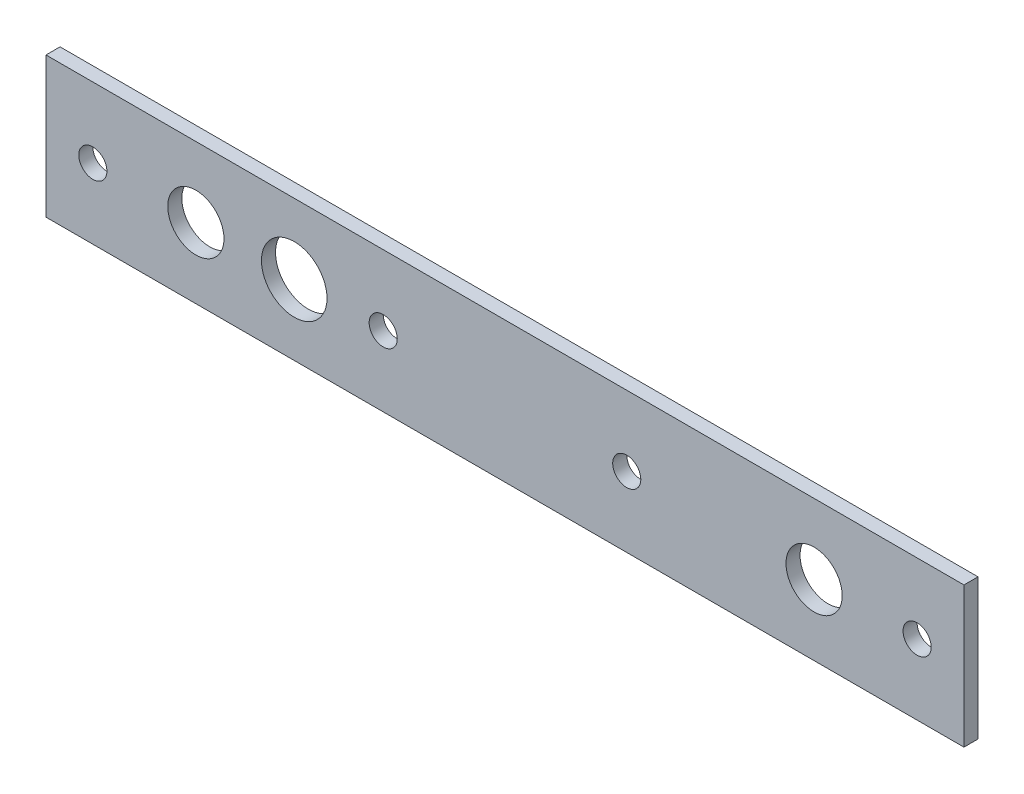
SolidWorks part; units mm, degrees
ref_plane "Plan de face" through (0, 0, 0) normal (0, 0, 1) x (1, 0, 0)
ref_plane "Plan de dessus" through (0, 0, 0) normal (0, 1, 0) x (1, 0, 0)
ref_plane "Plan de droite" through (0, 0, 0) normal (1, 0, 0) x (0, 0, -1)
sketch "Esquisse1" plane through (0, 0, 0) normal (0, 0, 1) x (1, 0, 0)
  line L0 (-44.8169, -6.8181) -> (53.1831, -6.8181)
  line L2 (53.1831, -6.8181) -> (53.1831, -21.8181)
  line L3 (53.1831, -21.8181) -> (-44.8169, -21.8181)
  line L4 (-44.8169, -21.8181) -> (-44.8169, -6.8181)
  circle A0 centre (-8.8169, -14.3181) radius 1.5
  circle A1 centre (17.1831, -14.3181) radius 1.5
  circle A2 centre (-28.8169, -14.3181) radius 3
  circle A3 centre (37.1831, -14.3181) radius 3
  circle A4 centre (-18.3169, -14.3181) radius 3.5
  circle A5 centre (48.1831, -14.3181) radius 1.5
  circle A6 centre (-39.8169, -14.3181) radius 1.5
  dimension "D6" = 7.5
  dimension "D10" = 7.5
  dimension "D13" = 5
  dimension "D2" = 7.5
  dimension "D5" = 10.5
  dimension "D12" = 5
  dimension "D1" = 15
  dimension "D3" = 16
  dimension "D4" = 98
  dimension "D7" = 7.5
  dimension "D8" = 36
  dimension "D9" = 36
  dimension "D11" = 16
extrude "Extrusion1" add sketch "Esquisse1" along normal blind 1.5
